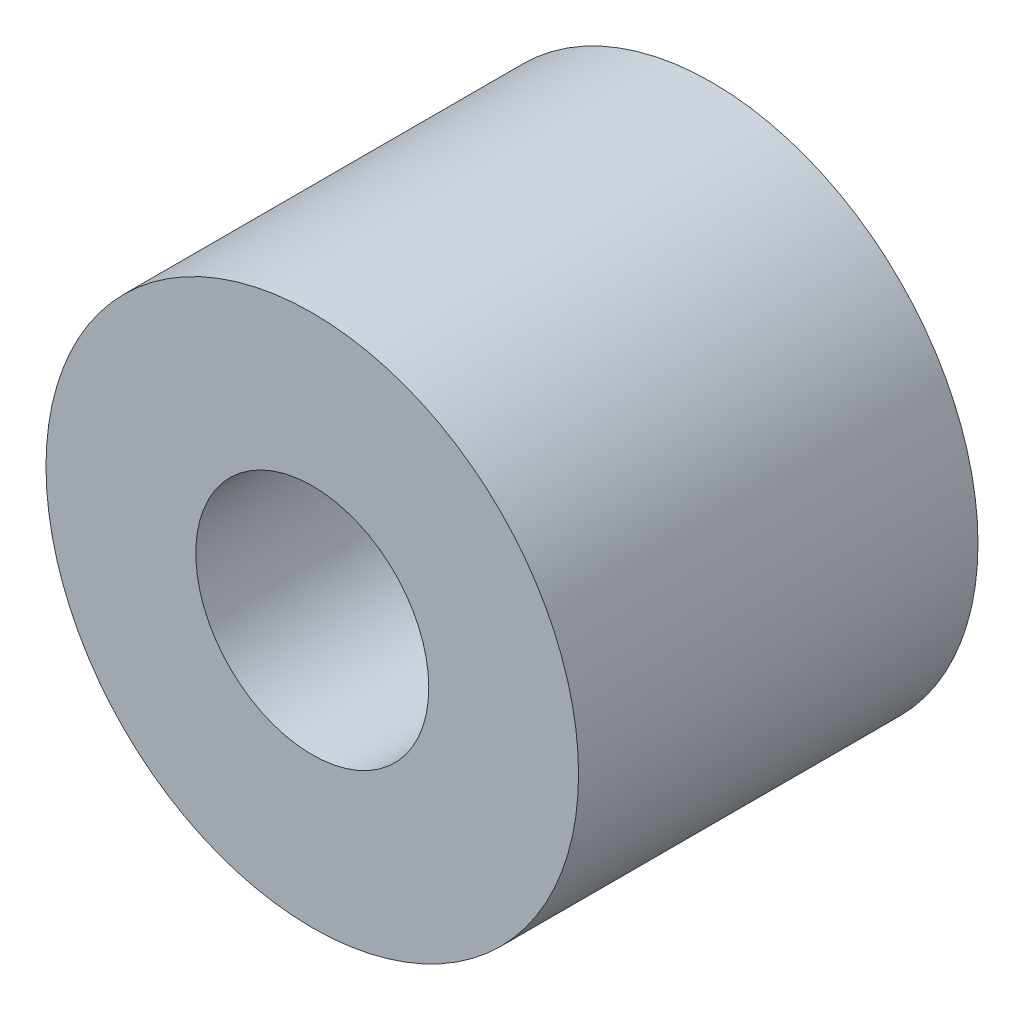
SolidWorks part; units mm, degrees
ref_plane "Alzado" through (0, 0, 0) normal (0, 0, 1) x (1, 0, 0)
ref_plane "Planta" through (0, 0, 0) normal (0, 1, 0) x (1, 0, 0)
ref_plane "Vista lateral" through (0, 0, 0) normal (1, 0, 0) x (0, 0, -1)
sketch "Croquis1" plane through (0, 0, 0) normal (0, 0, 1) x (1, 0, 0)
  circle A0 centre (0, 0) radius 4
  circle A1 centre (0, 0) radius 1.75
  dimension "D1" = 8
  dimension "D2" = 3.5
extrude "Saliente-Extruir1" add sketch "Croquis1" along normal blind 6
